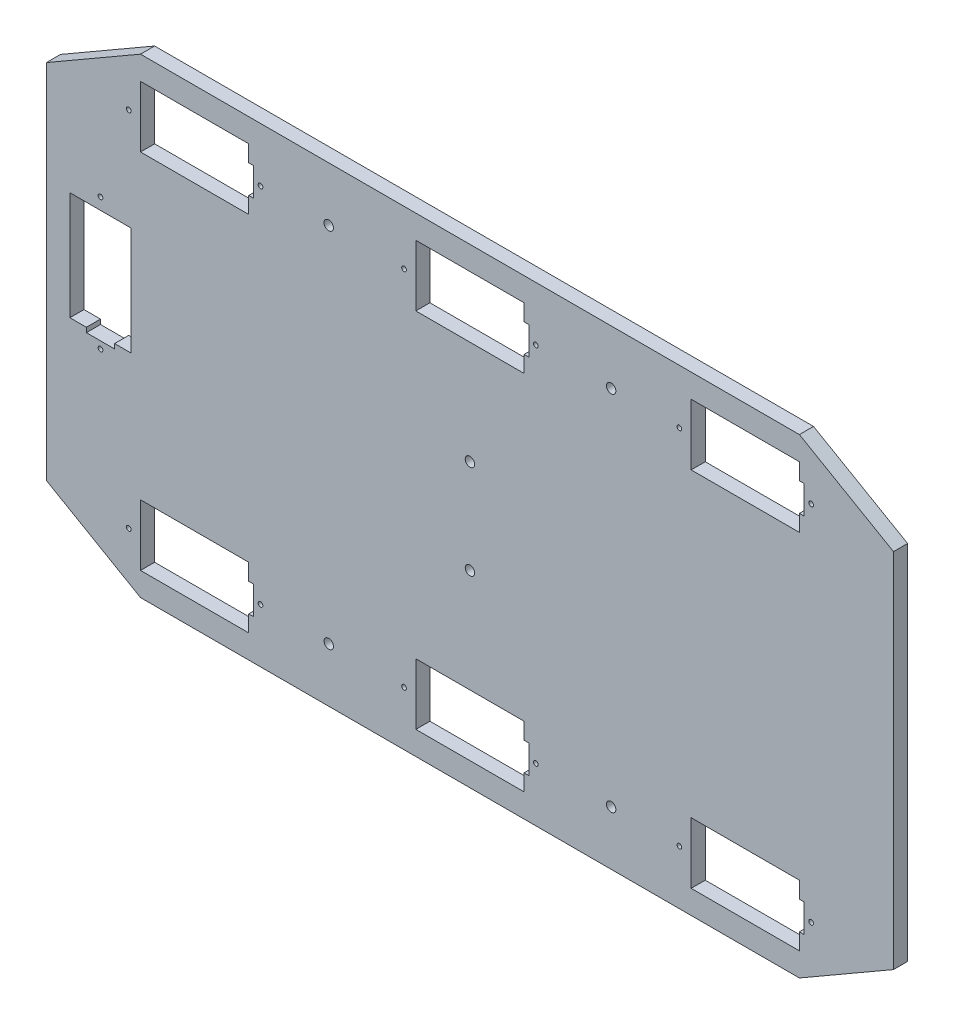
SolidWorks part; units mm, degrees
ref_plane "Front Plane" through (0, 0, 0) normal (0, 0, 1) x (1, 0, 0)
ref_plane "Top Plane" through (0, 0, 0) normal (0, 1, 0) x (1, 0, 0)
ref_plane "Right Plane" through (0, 0, 0) normal (1, 0, 0) x (0, 0, -1)
sketch "Sketch1" plane through (0, 0, 0) normal (0, 0, 1) x (1, 0, 0)
  line L0 (70, 50) -> (90, 38.453)
  line L1 (-70, 50) -> (70, 50)
  line L3 (-70, -50) -> (70, -50)
  line L5 (-70, 50) -> (70, -50) construction
  line L6 (-70, -50) -> (70, 50) construction
  line L7 (90, 38.453) -> (90, -38.453)
  line L8 (90, -38.453) -> (70, -50)
  line L9 (-70, 50) -> (-90, 38.453)
  line L10 (-90, 38.453) -> (-90, -38.453)
  line L11 (-90, -38.453) -> (-70, -50)
  point P0 (0, 0)
  dimension "D1" = 100
  dimension "D2" = 140
extrude "Boss-Extrude1" add sketch "Sketch1" along normal blind 3
sketch "Sketch2" plane through (0, 0, 3) normal (0, 0, 1) x (1, 0, 0)
  line L0 (0, 62.1255) -> (0, -58.115) construction
  line L1 (70, 50) -> (70, -50) construction
  line L2 (-70, 50) -> (-70, -50) construction
  line L3 (-70, -50) -> (70, -50) construction
  line L4 (-11.5, 45) -> (11.5, 45)
  line L5 (-11.5, 45) -> (-11.5, 32)
  line L6 (-11.5, 32) -> (11.5, 32)
  line L7 (11.5, 45) -> (11.5, 41.5)
  line L8 (-11.5, 45) -> (11.5, 32) construction
  line L9 (-11.5, 32) -> (11.5, 45) construction
  line L10 (-11.5, -32) -> (11.5, -32)
  line L11 (-11.5, -32) -> (-11.5, -45)
  line L12 (-11.5, -45) -> (11.5, -45)
  line L13 (11.5, -32) -> (11.5, -35.5)
  line L14 (-11.5, -32) -> (11.5, -45) construction
  line L15 (-11.5, -45) -> (11.5, -32) construction
  line L16 (-70, 45) -> (-47, 45)
  line L17 (-70, 45) -> (-70, 32)
  line L18 (-70, 32) -> (-47, 32)
  line L19 (-47, 45) -> (-47, 41.5)
  line L20 (-70, -32) -> (-47, -32)
  line L21 (-70, -32) -> (-70, -45)
  line L22 (-70, -45) -> (-47, -45)
  line L23 (-47, -32) -> (-47, -35.5)
  line L24 (70, -32) -> (47, -32)
  line L25 (70, -32) -> (70, -35.5)
  line L26 (70, -45) -> (47, -45)
  line L27 (47, -32) -> (47, -45)
  line L28 (70, 45) -> (47, 45)
  line L29 (70, 45) -> (70, 41.5)
  line L30 (70, 32) -> (47, 32)
  line L31 (47, 45) -> (47, 32)
  line L32 (70, 50) -> (-70, 50) construction
  line L33 (-77.4058, 38.5) -> (83.0739, 38.5) construction
  line L34 (-47, 35.5) -> (-46, 35.5)
  line L35 (-47, 35.5) -> (-47, 32)
  line L36 (-47, 41.5) -> (-46, 41.5)
  line L37 (-46, 35.5) -> (-46, 41.5)
  line L38 (-48, 35.5) -> (-46, 41.5) construction
  line L39 (-48, 41.5) -> (-46, 35.5) construction
  line L40 (11.5, 35.5) -> (12.5, 35.5)
  line L41 (11.5, 35.5) -> (11.5, 32)
  line L42 (11.5, 41.5) -> (12.5, 41.5)
  line L43 (12.5, 35.5) -> (12.5, 41.5)
  line L44 (10.5, 35.5) -> (12.5, 41.5) construction
  line L45 (10.5, 41.5) -> (12.5, 35.5) construction
  line L46 (70, 35.5) -> (71, 35.5)
  line L47 (70, 35.5) -> (70, 32)
  line L48 (70, 41.5) -> (71, 41.5)
  line L49 (71, 35.5) -> (71, 41.5)
  line L50 (69, 35.5) -> (71, 41.5) construction
  line L51 (69, 41.5) -> (71, 35.5) construction
  line L52 (70, -41.5) -> (71, -41.5)
  line L53 (70, -41.5) -> (70, -45)
  line L54 (70, -35.5) -> (71, -35.5)
  line L55 (71, -41.5) -> (71, -35.5)
  line L56 (69, -41.5) -> (71, -35.5) construction
  line L57 (69, -35.5) -> (71, -41.5) construction
  line L58 (11.5, -41.5) -> (12.5, -41.5)
  line L59 (11.5, -41.5) -> (11.5, -45)
  line L60 (11.5, -35.5) -> (12.5, -35.5)
  line L61 (12.5, -41.5) -> (12.5, -35.5)
  line L62 (10.5, -41.5) -> (12.5, -35.5) construction
  line L63 (10.5, -35.5) -> (12.5, -41.5) construction
  line L64 (-47, -41.5) -> (-46, -41.5)
  line L65 (-47, -41.5) -> (-47, -45)
  line L66 (-47, -35.5) -> (-46, -35.5)
  line L67 (-46, -41.5) -> (-46, -35.5)
  line L68 (-48, -41.5) -> (-46, -35.5) construction
  line L69 (-48, -35.5) -> (-46, -41.5) construction
  line L70 (76.3393, -38.5) -> (-79.8508, -38.5) construction
  circle A0 centre (-72.5, 38.5) radius 0.5
  circle A1 centre (-44.5, 38.5) radius 0.5
  circle A2 centre (-14, 38.5) radius 0.5
  circle A3 centre (14, 38.5) radius 0.5
  circle A4 centre (44.5, 38.5) radius 0.5
  circle A5 centre (72.5, 38.5) radius 0.5
  circle A6 centre (72.5, -38.5) radius 0.5
  circle A7 centre (44.5, -38.5) radius 0.5
  circle A8 centre (14, -38.5) radius 0.5
  circle A9 centre (-14, -38.5) radius 0.5
  circle A10 centre (-44.5, -38.5) radius 0.5
  circle A11 centre (-72.5, -38.5) radius 0.5
  circle A12 centre (0, 10) radius 1
  circle A13 centre (0, -10) radius 1
  point P11 (0, 38.5)
  point P16 (0, -38.5)
  point P41 (-47, 38.5)
  point P46 (11.5, 38.5)
  point P51 (70, 38.5)
  point P56 (70, -38.5)
  point P61 (11.5, -38.5)
  point P66 (-47, -38.5)
  dimension "D11" = 1
  dimension "D24" = 2
  dimension "D1" = 23
  dimension "D2" = 13
  dimension "D3" = 5
  dimension "D4" = 5
  dimension "D5" = 5
  dimension "D6" = 5
  dimension "D7" = 5
  dimension "D8" = 5
  dimension "D9" = 2
  dimension "D10" = 6
  dimension "D12" = 2.5
  dimension "D13" = 2.5
  dimension "D14" = 2.5
  dimension "D15" = 2.5
  dimension "D16" = 2.5
  dimension "D17" = 2.5
  dimension "D18" = 2.5
  dimension "D19" = 2.5
  dimension "D20" = 2.5
  dimension "D21" = 2.5
  dimension "D22" = 2.5
  dimension "D23" = 2.5
  dimension "D25" = 10
  dimension "D26" = 10
extrude "Cut-Extrude1" cut sketch "Sketch2" against normal up to next
sketch "Sketch3" plane through (0, 0, 3) normal (0, 0, 1) x (1, 0, 0)
  line L0 (-101.4234, 0) -> (115.3247, 0) construction
  line L1 (-90, 38.453) -> (-90, -38.453) construction
  line L2 (-85, 17) -> (-72, 17)
  line L3 (-85, 17) -> (-85, -6)
  line L4 (-85, -6) -> (-81.5, -6)
  line L5 (-72, 17) -> (-72, -6)
  line L6 (-85, 17) -> (-72, -6) construction
  line L7 (-85, -6) -> (-72, 17) construction
  line L8 (-78.5, 25.4202) -> (-78.5, -22.4327) construction
  line L9 (-75.5, -6) -> (-72, -6)
  line L10 (-81.5, -6) -> (-81.5, -7)
  line L11 (-81.5, -7) -> (-75.5, -7)
  line L12 (-75.5, -6) -> (-75.5, -7)
  line L13 (-81.5, -5) -> (-75.5, -7) construction
  line L14 (-81.5, -7) -> (-75.5, -5) construction
  circle A0 centre (-78.5, 19.5) radius 0.5
  circle A1 centre (-78.5, -8.5) radius 0.5
  point P3 (-78.5, 5.5)
  point P11 (-78.5, -6)
  dimension "D7" = 1
  dimension "D1" = 13
  dimension "D2" = 23
  dimension "D3" = 5
  dimension "D4" = 6
  dimension "D5" = 2
  dimension "D6" = 6
  dimension "D8" = 2.5
  dimension "D9" = 2.5
extrude "Cut-Extrude2" cut sketch "Sketch3" against normal up to next
sketch "Sketch5" plane through (0, 0, 0) normal (0, 0, -1) x (-1, 0, 0)
  line L0 (-83.9747, 38.5) -> (103.5165, 38.5) construction
  line L1 (79.7826, -38.5) -> (-79.0541, -38.5) construction
  line L2 (0, 65.9392) -> (0, -105.4584) construction
  circle A0 centre (30, 38.5) radius 1
  circle A1 centre (-30, 38.5) radius 1
  circle A2 centre (30, -38.5) radius 1
  circle A3 centre (-30, -38.5) radius 1
  dimension "D1" = 2
  dimension "D2" = 30
  dimension "D3" = 30
  dimension "D4" = 30
  dimension "D5" = 30
extrude "Cut-Extrude3" cut sketch "Sketch5" against normal up to next
